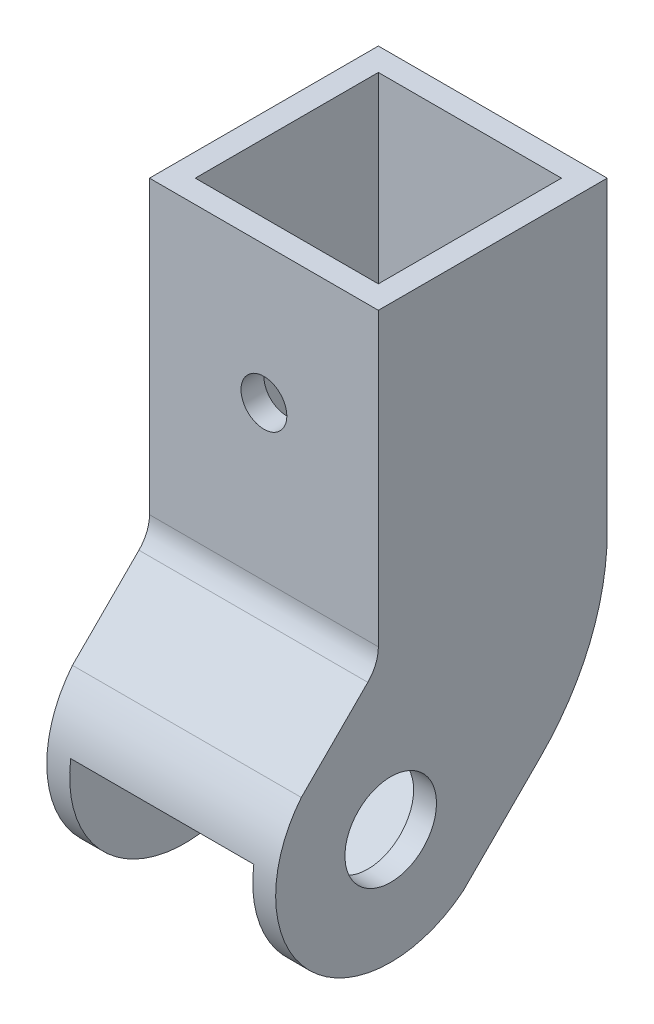
SolidWorks part; units mm, degrees
material "6061-T6 (SS)"
ref_plane "Front Plane" through (0, 0, 0) normal (0, 0, 1) x (1, 0, 0)
ref_plane "Top Plane" through (0, 0, 0) normal (0, 1, 0) x (1, 0, 0)
ref_plane "Right Plane" through (0, 0, 0) normal (1, 0, 0) x (0, 0, -1)
sketch "Sketch1" plane through (0, 0, 0) normal (1, 0, 0) x (0, 0, -1)
  line L1 (15.875, -42.5) -> (-15.875, -42.5) construction
  line L2 (15.875, -42.5) -> (15.875, 42.5) construction
  line L3 (15.875, 42.5) -> (-15.875, 42.5)
  line L4 (-15.875, -42.5) -> (-15.875, 42.5) construction
  line L5 (15.875, -42.5) -> (-15.875, 42.5) construction
  line L6 (15.875, 42.5) -> (-15.875, -42.5) construction
  line L7 (-15.875, 42.5) -> (-15.875, 0)
  line L8 (15.875, 42.5) -> (15.875, 0)
  line L10 (-16.4053, -45.4316) -> (-38.856, -22.981)
  line L11 (-38.856, -22.981) -> (-15.875, 0)
  line L12 (-16.4053, -45.4316) -> (6.5756, -22.4506)
  arc A0 (15.875, 0) -> (6.5756, -22.4506) centre (-15.875, 0) cw
  point P0 (0, 0)
  dimension "D1" = 31.75
  dimension "D2" = 85
  dimension "D3" = 135
  dimension "D4" = 32.5
extrude "Boss-Extrude1" add sketch "Sketch1" along normal blind 31.75
sketch "Sketch3" plane through (0, 0, 0) normal (-1, 0, 0) x (0, 0, 1)
  line L30 (16.4053, -40.9415) -> (34.3658, -22.981)
  line L31 (-4.3306, -20.2056) -> (16.4053, -40.9415)
  line L32 (34.3658, -22.981) -> (12.7, -1.3151)
  line L33 (12.7, -1.3151) -> (12.7, 39.325)
  line L34 (-12.7, 39.325) -> (-12.7, 0)
  line L35 (12.7, 39.325) -> (-12.7, 39.325)
  line L36 (16.4053, -40.9415) -> (34.3658, -22.981)
  line L37 (-4.3306, -20.2056) -> (16.4053, -40.9415)
  line L38 (34.3658, -22.981) -> (12.7, -1.3151)
  line L39 (12.7, -1.3151) -> (12.7, 39.325)
  line L40 (-12.7, 39.325) -> (-12.7, 0)
  line L41 (12.7, 39.325) -> (-12.7, 39.325)
  arc A5 (-12.7, 0) -> (-4.3306, -20.2056) centre (15.875, 0) ccw
  arc A6 (-12.7, 0) -> (-4.3306, -20.2056) centre (15.875, 0) ccw
  dimension "D1" = 3.175
extrude "Cut-Extrude2" cut sketch "Sketch3" against normal offset from surface (25.4 mm away) 3.175 from offset 3.175 up to face at (31.75, -0.9697, 6.6361) offset against normal yes
sketch "Sketch4" plane through (0, 42.5, 0) normal (0, 1, 0) x (1, 0, 0)
  line L14 (3.175, -12.7) -> (28.575, -12.7)
  line L15 (3.175, 12.7) -> (3.175, -12.7)
  line L16 (28.575, -12.7) -> (28.575, 12.7)
  line L17 (28.575, 12.7) -> (3.175, 12.7)
  line L18 (3.175, -12.7) -> (28.575, -12.7)
  line L19 (3.175, 12.7) -> (3.175, -12.7)
  line L20 (28.575, -12.7) -> (28.575, 12.7)
  line L21 (28.575, 12.7) -> (3.175, 12.7)
  dimension "D1" = 3.175
extrude "Cut-Extrude3" cut sketch "Sketch4" against normal blind 3.175
sketch "Sketch6" plane through (0, -30.9185, 30.9185) normal (0, -0.7071, 0.7071) x (1, 0, 0)
  line L14 (3.175, 8.0503) -> (3.175, -17.3497)
  line L15 (3.175, -17.3497) -> (28.575, -17.3497)
  line L16 (28.575, -17.3497) -> (28.575, 8.0503)
  line L17 (28.575, 8.0503) -> (3.175, 8.0503)
  line L18 (3.175, 8.0503) -> (3.175, -17.3497)
  line L19 (3.175, -17.3497) -> (28.575, -17.3497)
  line L20 (28.575, -17.3497) -> (28.575, 8.0503)
  line L21 (28.575, 8.0503) -> (3.175, 8.0503)
  dimension "D1" = 3.175
extrude "Cut-Extrude5" cut sketch "Sketch6" against normal blind 3.175
fillet "Fillet1" radius 5 2 edges at (15.875, -1.3151, 12.7) (15.875, 0, 15.875)
sketch "Sketch8" plane through (0, 0, -15.875) normal (0, 0, -1) x (-1, 0, 0)
  line L1 (-31.75, 42.5) -> (0, 42.5) construction
  line L2 (-15.875, 42.5) -> (-15.875, 0) construction
  line L3 (-31.75, 0) -> (0, 0) construction
  circle A0 centre (-15.875, 23.45) radius 3.175
  dimension "D2" = 6.35
  dimension "D3" = 19.05
extrude "Cut-Extrude6" cut sketch "Sketch8" against normal up to surface (31.75 mm away) up to face at (15.875, 22.2855, 15.875)
sketch "Sketch9" plane through (31.75, 0, 0) normal (1, 0, 0) x (0, 0, -1)
  line L0 (-16.4053, -45.4316) -> (6.5756, -22.4506) construction
  line L1 (-38.856, -22.981) -> (-16.4053, -45.4316) construction
  circle A0 centre (-14.1603, -20.7359) radius 6.35
  dimension "D2" = 12.7
  dimension "D1" = 15.875
  dimension "D3" = 19.05
extrude "Cut-Extrude7" cut sketch "Sketch9" against normal up to surface (31.75 mm away) up to face at (0, -0.7909, 7.9301)
sketch "Sketch11" plane through (31.75, 0, 0) normal (1, 0, 0) x (0, 0, -1)
  line L0 (-17.3395, -1.4645) -> (-38.856, -22.981) construction
  line L1 (-16.4053, -45.4316) -> (6.5756, -22.4506) construction
  line L3 (-26.5606, -10.6856) -> (-38.856, -22.981)
  line L4 (-38.856, -22.981) -> (-16.4053, -45.4316)
  line L5 (-16.4053, -45.4316) -> (-1.7599, -30.7862)
  arc A0 (-26.5606, -10.6856) -> (-1.7599, -30.7862) centre (-14.1603, -20.7359) ccw
  line M5 (-17.3395, -1.4645) -> (-38.856, -22.981)
  line M6 (-38.856, -22.981) -> (-16.4053, -45.4316)
  line M7 (-16.4053, -45.4316) -> (6.5756, -22.4506)
  dimension "D1" = 12.2954
extrude "Cut-Extrude8" cut sketch "Sketch11" against normal through all contours A0 M5 M6 M7
